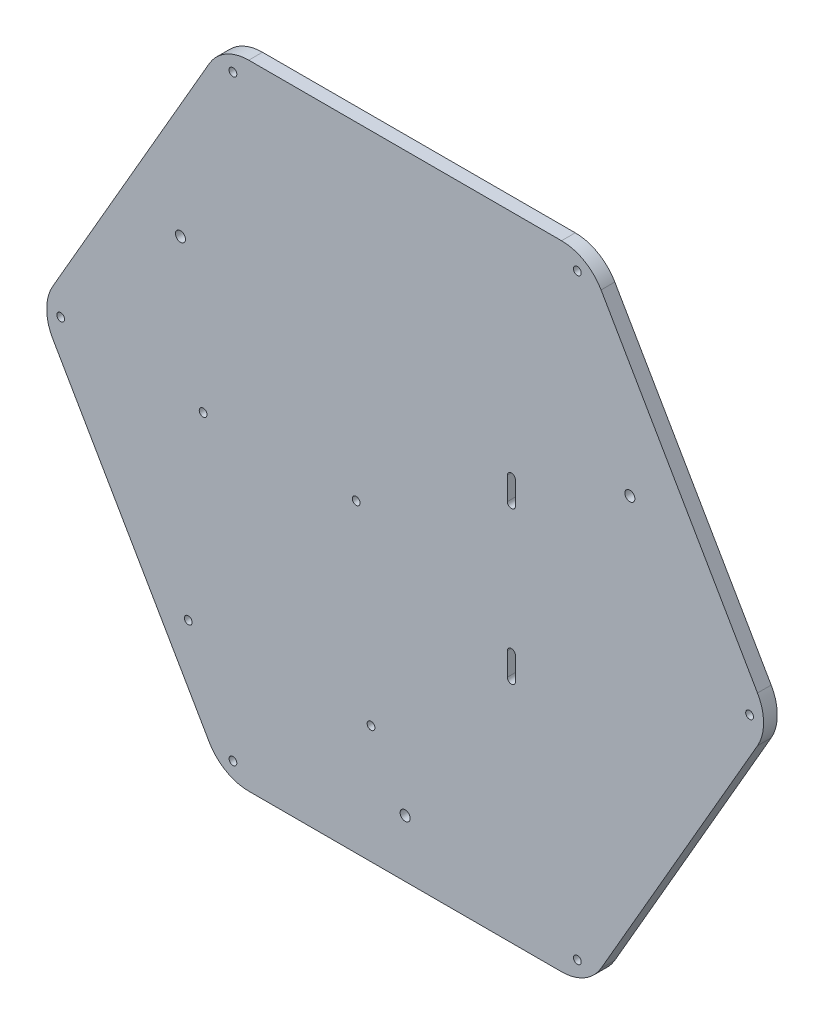
SolidWorks part; units mm, degrees
material "PP Homopolymer"
ref_plane "Front Plane" through (0, 0, 0) normal (0, 0, 1) x (1, 0, 0)
ref_plane "Top Plane" through (0, 0, 0) normal (0, 1, 0) x (1, 0, 0)
ref_plane "Right Plane" through (0, 0, 0) normal (1, 0, 0) x (0, 0, -1)
sketch "Sketch1" plane through (0, 0, 0) normal (0, 0, 1) x (1, 0, 0)
  line L1 (80, 138.5641) -> (-80, 138.5641)
  line L2 (-80, 138.5641) -> (-160, 0)
  line L3 (-160, 0) -> (-80, -138.5641)
  line L4 (-80, -138.5641) -> (80, -138.5641)
  line L5 (80, -138.5641) -> (160, 0)
  line L6 (160, 0) -> (80, 138.5641)
  circle A0 centre (0, 0) radius 138.5641 construction
  dimension "D1" = 160
extrude "Boss-Extrude1" add sketch "Sketch1" along normal blind 6
fillet "Fillet1" radius 20 6 edges at (80, 138.5641, 3) (-80, 138.5641, 3) (-160, 0, 3) (-80, -138.5641, 3) (80, -138.5641, 3) (160, 0, 3)
sketch "Sketch9" plane through (0, 0, 6) normal (0, 0, 1) x (1, 0, 0)
  line L0 (-68.453, -138.5641) -> (68.453, -138.5641) construction
  line L1 (-78.453, -135.8846) -> (0, 0) construction
  line L2 (0, -138.5641) -> (0, 0) construction
  line L3 (-78.453, 135.8846) -> (0, 0) construction
  line L4 (-120, 69.282) -> (0, 0) construction
  line L5 (156.906, 0) -> (0, 0) construction
  line L6 (120, 69.282) -> (0, 0) construction
  circle A0 centre (-75.3812, -130.5641) radius 1.7
  arc A1 (-85.7735, -128.5641) -> (-68.453, -138.5641) centre (-68.453, -118.5641) ccw construction
  circle A2 centre (75.3812, -130.5641) radius 1.7
  circle A3 centre (-75.3812, 130.5641) radius 1.7
  circle A4 centre (-150.7624, 0) radius 1.7
  circle A5 centre (150.7624, 0) radius 1.7
  circle A6 centre (75.3812, 130.5641) radius 1.7
  point P28 (0, 0)
  dimension "D2" = 3.4
  dimension "D1" = 8
extrude "Cut-Extrude7" cut sketch "Sketch9" against normal blind 70
sketch "Sketch10" plane through (0, 0, 6) normal (0, 0, 1) x (1, 0, 0)
  line L6 (-156.906, 0) -> (156.906, 0) construction
  line L7 (-94.9374, -87) -> (-14.9374, -87) construction
  line L8 (-54.9374, -5) -> (-21.4374, -5) construction
  line L9 (-54.9374, -87) -> (-54.9374, -5) construction
  arc A6 (-154.2265, 10) -> (-154.2265, -10) centre (-136.906, 0) ccw construction
  arc A7 (154.2265, -10) -> (154.2265, 10) centre (136.906, 0) ccw construction
  circle A8 centre (-88.4374, -5) radius 1.7
  circle A9 centre (-21.4374, -5) radius 1.7
  circle A10 centre (-14.9374, -87) radius 1.7
  circle A11 centre (-94.9374, -87) radius 1.7
extrude "Cut-Extrude8" cut sketch "Sketch10" against normal blind 10
sketch "Sketch11" plane through (0, 0, 6) normal (0, 0, 1) x (1, 0, 0)
  line L1 (46.5, 37.8084) -> (46.5, 27.8084) construction
  line L2 (46.5, -33.75) -> (93.5, -33.75) construction
  line L3 (46.5, -33.75) -> (46.5, 33.75) construction
  line L4 (46.5, 33.75) -> (93.5, 33.75) construction
  line L5 (93.5, -33.75) -> (93.5, 33.75) construction
  line L6 (46.5, -33.75) -> (93.5, 33.75) construction
  line L7 (46.5, 33.75) -> (93.5, -33.75) construction
  line L8 (48.25, 37.8084) -> (48.25, 27.8084)
  line L9 (44.75, 37.8084) -> (44.75, 27.8084)
  line L10 (46.5, -38.75) -> (46.5, -28.75) construction
  line L11 (48.25, -38.75) -> (48.25, -28.75)
  line L12 (44.75, -38.75) -> (44.75, -28.75)
  arc A4 (48.25, 37.8084) -> (44.75, 37.8084) centre (46.5, 37.8084) ccw
  arc A5 (44.75, 27.8084) -> (48.25, 27.8084) centre (46.5, 27.8084) ccw
  arc A6 (48.25, -38.75) -> (44.75, -38.75) centre (46.5, -38.75) cw
  arc A7 (44.75, -28.75) -> (48.25, -28.75) centre (46.5, -28.75) cw
  point P6 (70, 0)
  point P15 (46.5, 32.8084)
  point P20 (46.5, -33.75)
  dimension "D1" = 70
  dimension "D6" = 1.75
  dimension "D3" = 47
  dimension "D4" = 67.5
  dimension "D5" = 10
extrude "Cut-Extrude9" cut sketch "Sketch11" against normal blind 10
sketch "Sketch12" plane through (0, 0, 6) normal (0, 0, 1) x (1, 0, 0)
  circle A0 centre (0, -113.5641) radius 2.2
  circle A1 centre (-98.3494, 56.782) radius 2.2
  circle A2 centre (98.3494, 56.782) radius 2.2
  point P10 (0, 0)
  dimension "D1" = 3
extrude "Cut-Extrude10" cut sketch "Sketch12" against normal blind 10
